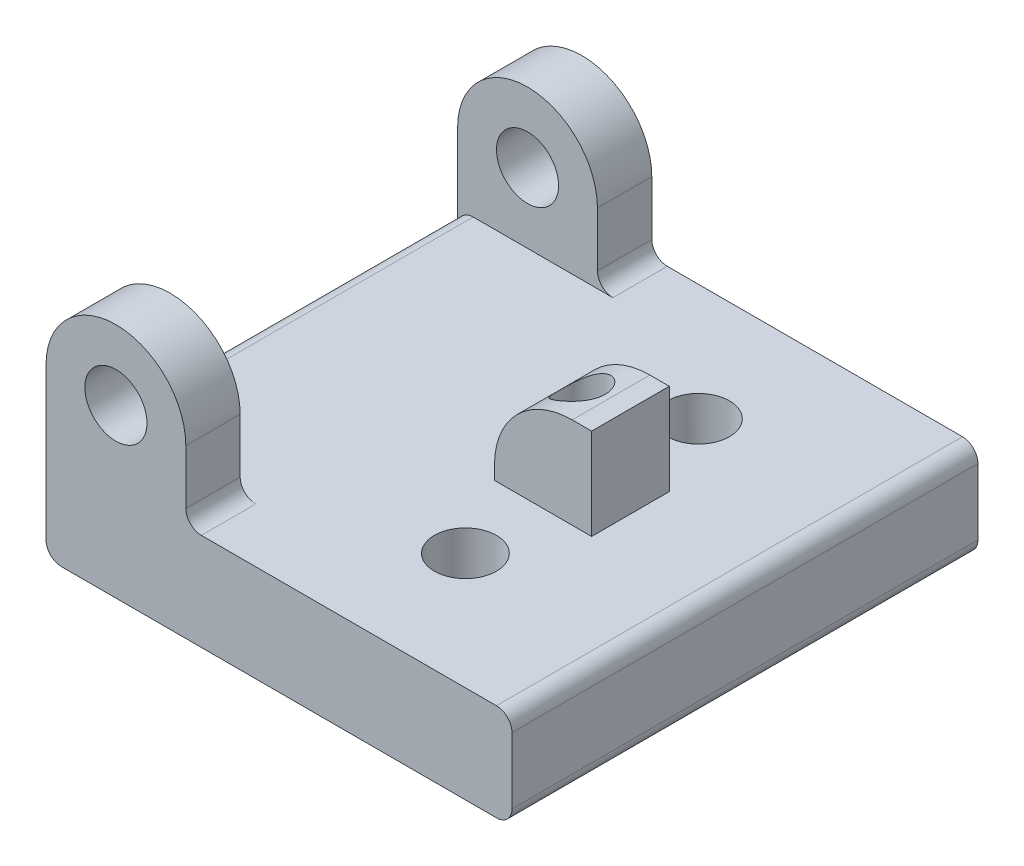
SolidWorks part; units mm, degrees
material "6061-O (SS)"
ref_plane "Front Plane" through (0, 0, 0) normal (0, 0, 1) x (1, 0, 0)
ref_plane "Top Plane" through (0, 0, 0) normal (0, 1, 0) x (1, 0, 0)
ref_plane "Right Plane" through (0, 0, 0) normal (1, 0, 0) x (0, 0, -1)
sketch "Sketch1" plane through (0, 0, 0) normal (0, 0, 1) x (1, 0, 0)
  line L0 (-37, -11.75) -> (19, -11.75)
  line L1 (21, -9.75) -> (21, -1.25)
  line L2 (19, 0.75) -> (-19, 0.75)
  line L3 (-21, 2.75) -> (-21, 9.75)
  line L4 (-39, 9.75) -> (-39, -9.75)
  arc A0 (-21, 9.75) -> (-39, 9.75) centre (-30, 9.75) ccw
  arc A1 (-39, -9.75) -> (-37, -11.75) centre (-37, -9.75) ccw
  arc A2 (19, -11.75) -> (21, -9.75) centre (19, -9.75) ccw
  arc A3 (21, -1.25) -> (19, 0.75) centre (19, -1.25) ccw
  arc A4 (-19, 0.75) -> (-21, 2.75) centre (-19, 2.75) cw
  circle A5 centre (-30, 9.75) radius 4
  point P16 (-39, 0)
  point P17 (0, 0.75)
  dimension "D3" = 9
  dimension "D5" = 2
  dimension "D6" = 8
  dimension "D1" = 12.5
  dimension "D2" = 60
  dimension "D4" = 9
extrude "Boss-Extrude2" add sketch "Sketch1" against normal blind 7
ref_plane "Plane1" through (0, 0, -7) normal (0, 0, -1) x (-1, 0, 0)
sketch "Sketch4" plane through (0, 0, -7) normal (0, 0, -1) x (-1, 0, 0)
  line L3 (19, 0.75) -> (37, 0.75)
  line L4 (39, 9.75) -> (39, -9.75) construction
  line L5 (21, 9.75) -> (21, 2.75)
  line L6 (19, 0.75) -> (-19, 0.75)
  line L7 (-21, -1.25) -> (-21, -9.75)
  line L8 (-19, -11.75) -> (37, -11.75)
  line L9 (39, -9.75) -> (39, 9.75)
  line L11 (19, 0.75) -> (-19, 0.75)
  line L12 (-21, -1.25) -> (-21, -9.75)
  line L13 (-19, -11.75) -> (37, -11.75)
  line L14 (39, -1.25) -> (39, -9.75)
  arc A0 (37, 0.75) -> (39, -1.25) centre (37, -1.25) cw
  arc A5 (39, 9.75) -> (21, 9.75) centre (30, 9.75) ccw
  arc A6 (19, 0.75) -> (21, 2.75) centre (19, 2.75) ccw
  arc A7 (-19, 0.75) -> (-21, -1.25) centre (-19, -1.25) ccw
  arc A8 (-21, -9.75) -> (-19, -11.75) centre (-19, -9.75) ccw
  arc A9 (37, -11.75) -> (39, -9.75) centre (37, -9.75) ccw
  arc A12 (-19, 0.75) -> (-21, -1.25) centre (-19, -1.25) ccw
  arc A13 (-21, -9.75) -> (-19, -11.75) centre (-19, -9.75) ccw
  arc A14 (37, -11.75) -> (39, -9.75) centre (37, -9.75) ccw
  dimension "D1" = 0
extrude "Boss-Extrude3" add sketch "Sketch4" along normal blind 23
ref_plane "Plane2" through (0, 0, -30) normal (0, 0, -1) x (-1, 0, 0)
mirror "Mirror2" about plane through (0, 0, -30) normal (0, 0, -1) of "Boss-Extrude3", "Boss-Extrude2"
mirror "Mirror3" about plane through (0, 0, -30) normal (0, 0, -1) of "Boss-Extrude2"
sketch "Sketch5" plane through (0, 0, 0) normal (0, 1, 0) x (1, 0, 0)
  line L0 (-49.1527, 30) -> (38.4955, 30) construction
  line L1 (55, 30) -> (-55, 30) construction
  circle A0 centre (0, 45) radius 4
  circle A1 centre (0, 15) radius 4
  dimension "D1" = 8
  dimension "D2" = 15
extrude "Cut-Extrude1" cut sketch "Sketch5" against normal through all both and the other way through all
sketch "Sketch6" plane through (0, 0, 0) normal (0, 1, 0) x (1, 0, 0)
  line L0 (0, 60) -> (0, 0) construction
  line L1 (-6.25, 35) -> (6.25, 35)
  line L2 (-6.25, 35) -> (-6.25, 25)
  line L3 (-6.25, 25) -> (6.25, 25)
  line L4 (6.25, 35) -> (6.25, 25)
  line L5 (19, 60) -> (-19, 60) construction
  point P9 (0, 35)
  point P10 (0, 25)
  point P11 (6.25, 30)
  dimension "D1" = 30
  dimension "D2" = 10
  dimension "D3" = 12.5
extrude "Boss-Extrude4" add sketch "Sketch6" along normal blind 12.5
fillet "Fillet1" radius 10 1 edges at (-6.25, 12.5, -30)
ref_plane "Plane3" through (0, 12.5, 0) normal (0, 1, 0) x (1, 0, 0)
sketch "Sketch8" plane through (0, 12.5, 0) normal (0, 1, 0) x (1, 0, 0)
  line L0 (-6.25, 25) -> (-6.25, 35) construction
  circle A0 centre (0, 30) radius 3
  point P5 (-6.25, 30)
  dimension "D1" = 6
extrude "Cut-Extrude2" cut sketch "Sketch8" against normal blind 15
